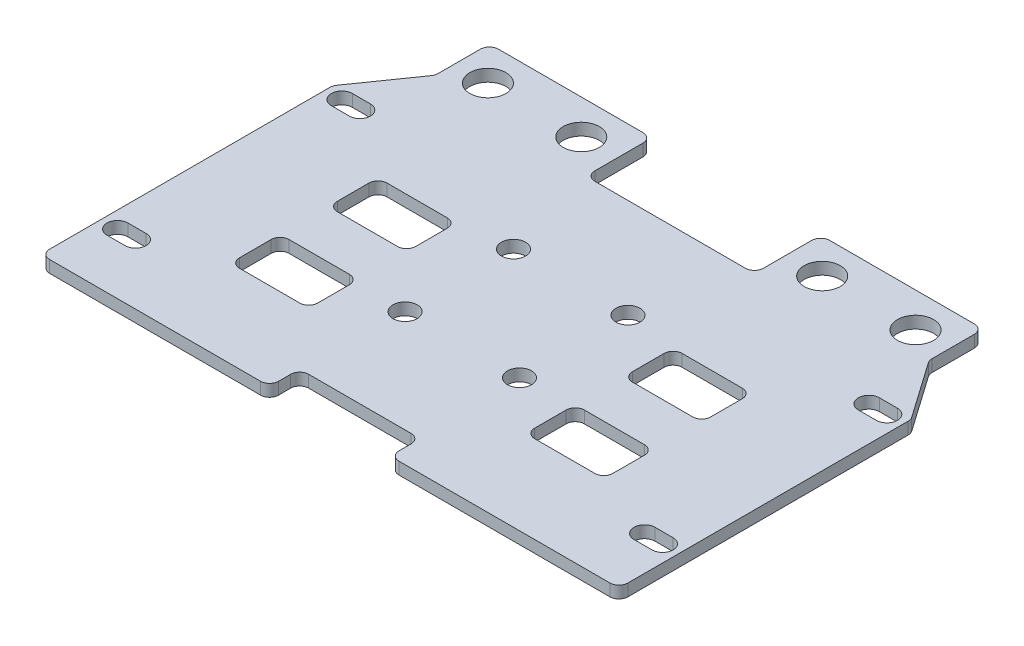
SolidWorks part; units mm, degrees
material "1060 Alloy"
ref_plane "Front Plane" through (0, 0, 0) normal (0, 0, 1) x (1, 0, 0)
ref_plane "Top Plane" through (0, 0, 0) normal (0, 1, 0) x (1, 0, 0)
ref_plane "Right Plane" through (0, 0, 0) normal (1, 0, 0) x (0, 0, -1)
sketch "Sketch1" plane through (0, 0, 0) normal (0, 1, 0) x (1, 0, 0)
  line L0 (38, 0) -> (38, 5)
  line L1 (0, 0) -> (38, 0)
  line L2 (0, 0) -> (0, 48.5)
  line L3 (7, 67.5) -> (34, 67.5)
  line L4 (96, 0) -> (96, 48.5)
  line L5 (0, 48.5) -> (7, 58.5)
  line L6 (7, 58.5) -> (7, 67.5)
  line L7 (34, 67.5) -> (34, 56.5)
  line L8 (48, -139.8616) -> (48, 139.8616) construction
  line L9 (58, 0) -> (58, 5)
  line L10 (96, 48.5) -> (89, 58.5)
  line L11 (89, 58.5) -> (89, 67.5)
  line L12 (62, 67.5) -> (62, 56.5)
  line L13 (38, 5) -> (58, 5)
  line L14 (58, 0) -> (96, 0)
  line L15 (34, 56.5) -> (62, 56.5)
  line L16 (62, 67.5) -> (89, 67.5)
  line L17 (79, 14.5) -> (66, 14.5)
  line L18 (17, 39) -> (30, 39)
  line L19 (17, 39) -> (17, 30.75)
  line L20 (17, 30.75) -> (30, 30.75)
  line L21 (30, 39) -> (30, 30.75)
  line L22 (17, 22.75) -> (30, 22.75)
  line L23 (17, 22.75) -> (17, 14.5)
  line L24 (17, 14.5) -> (30, 14.5)
  line L25 (30, 22.75) -> (30, 14.5)
  line L26 (66, 22.75) -> (66, 14.5)
  line L27 (79, 22.75) -> (66, 22.75)
  line L28 (79, 22.75) -> (79, 14.5)
  line L29 (79, 30.75) -> (66, 30.75)
  line L30 (66, 39) -> (66, 30.75)
  line L31 (79, 39) -> (66, 39)
  line L32 (79, 39) -> (79, 30.75)
  line L33 (2.75, 11.75) -> (5.75, 11.75)
  line L34 (2.75, 8.25) -> (5.75, 8.25)
  line L35 (93.25, 8.25) -> (90.25, 8.25)
  line L36 (93.25, 11.75) -> (90.25, 11.75)
  line L37 (-107.8769, 28.625) -> (107.8769, 28.625) construction
  line L38 (93.25, 45.5) -> (90.25, 45.5)
  line L39 (93.25, 49) -> (90.25, 49)
  line L40 (2.75, 49) -> (5.75, 49)
  line L41 (2.75, 45.5) -> (5.75, 45.5)
  circle A0 centre (38.5, 40) radius 2
  circle A1 centre (38.5, 22) radius 2
  circle A2 centre (57.5, 22) radius 2
  circle A3 centre (57.5, 40) radius 2
  arc A4 (2.75, 11.75) -> (2.75, 8.25) centre (2.75, 10) ccw
  arc A5 (5.75, 8.25) -> (5.75, 11.75) centre (5.75, 10) ccw
  arc A6 (93.25, 11.75) -> (93.25, 8.25) centre (93.25, 10) cw
  arc A7 (90.25, 8.25) -> (90.25, 11.75) centre (90.25, 10) cw
  arc A8 (93.25, 45.5) -> (93.25, 49) centre (93.25, 47.25) ccw
  arc A9 (90.25, 49) -> (90.25, 45.5) centre (90.25, 47.25) ccw
  arc A10 (2.75, 45.5) -> (2.75, 49) centre (2.75, 47.25) cw
  arc A11 (5.75, 49) -> (5.75, 45.5) centre (5.75, 47.25) cw
  circle A12 centre (12.5, 61.75) radius 3
  circle A13 centre (28, 61.75) radius 3
  circle A14 centre (68, 61.75) radius 3
  circle A15 centre (83.5, 61.75) radius 3
  point P14 (48, 0)
  point P59 (0, 28.625)
  dimension "D18" = 4
  dimension "D22" = 3.5
  dimension "D23" = 10
  dimension "D24" = 2.75
  dimension "D25" = 3.5
  dimension "D28" = 6
  dimension "D29" = 5.75
  dimension "D31" = 15.5
  dimension "D1" = 96
  dimension "D2" = 27
  dimension "D3" = 38
  dimension "D4" = 5
  dimension "D5" = 19
  dimension "D6" = 7
  dimension "D7" = 10
  dimension "D8" = 11
  dimension "D9" = 67.5
  dimension "D10" = 8.25
  dimension "D11" = 8.25
  dimension "D12" = 13
  dimension "D13" = 13
  dimension "D14" = 17
  dimension "D15" = 17
  dimension "D16" = 14.5
  dimension "D17" = 8
  dimension "D19" = 16.5
  dimension "D20" = 8.5
  dimension "D21" = 18
  dimension "D26" = 3
  dimension "D27" = 18.625
  dimension "D30" = 5.5
extrude "Boss-Extrude1" add sketch "Sketch1" along normal blind 2
fillet "Fillet1" radius 1.5 32 edges at (17, 1, -30.75) (17, 1, -14.5) (17, 1, -22.75) (17, 1, -39) (66, 1, -22.75) (66, 1, -39) (66, 1, -30.75) (66, 1, -14.5) (79, 1, -14.5) (79, 1, -30.75) (79, 1, -39) (79, 1, -22.75) (30, 1, -22.75) (30, 1, -14.5) (30, 1, -30.75) (30, 1, -39) (38, 1, -5) (58, 1, -5) (96, 1, -48.5) (89, 1, -58.5) (89, 1, -67.5) (62, 1, -67.5) (62, 1, -56.5) (34, 1, -56.5) (34, 1, -67.5) (7, 1, -67.5) (7, 1, -58.5) (0, 1, -48.5) (0, 1, 0) (96, 1, 0) (58, 1, 0) (38, 1, 0)
